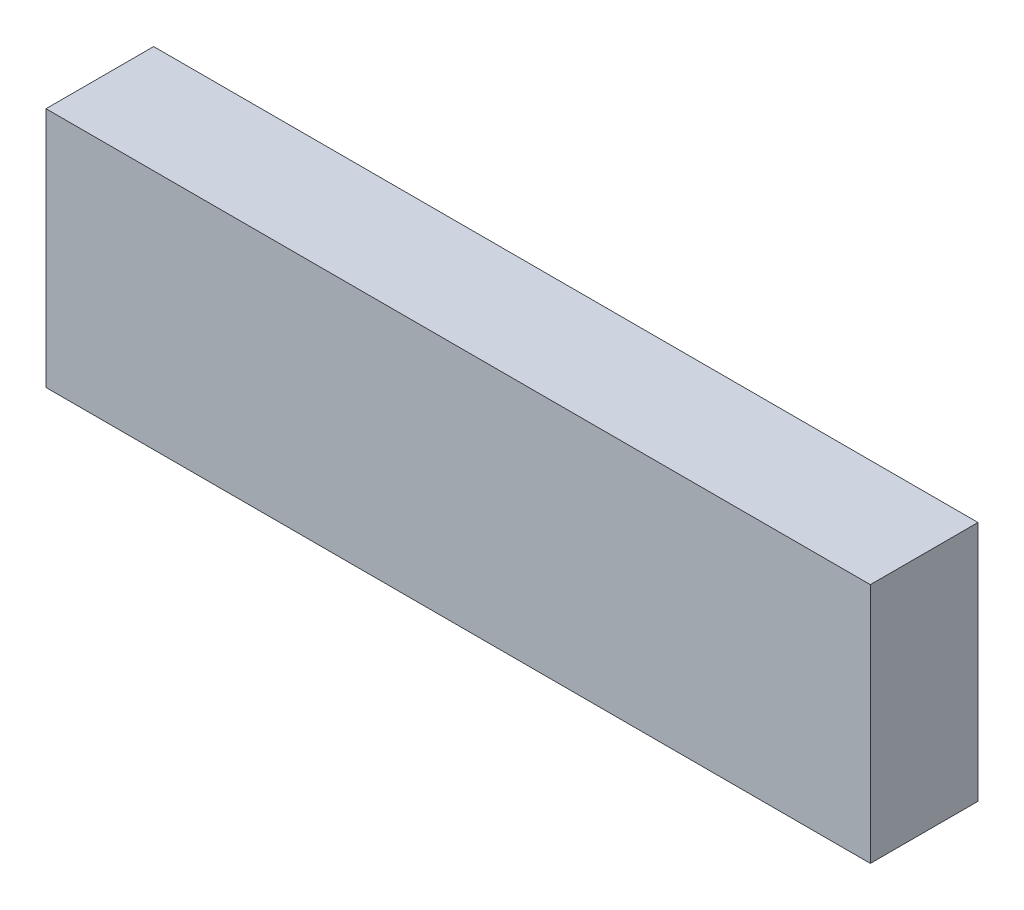
SolidWorks part; units mm, degrees
ref_plane "Front Plane" through (0, 0, 0) normal (0, 0, 1) x (1, 0, 0)
ref_plane "Top Plane" through (0, 0, 0) normal (0, 1, 0) x (1, 0, 0)
ref_plane "Right Plane" through (0, 0, 0) normal (1, 0, 0) x (0, 0, -1)
sketch "Sketch1" plane through (0, 0, 0) normal (0, 0, 1) x (1, 0, 0)
  line L1 (-60.5857, 19.8572) -> (207.4143, 19.8572)
  line L2 (-60.5857, 19.8572) -> (-60.5857, -58.6428)
  line L3 (-60.5857, -58.6428) -> (207.4143, -58.6428)
  line L4 (207.4143, 19.8572) -> (207.4143, -58.6428)
  dimension "D1" = 268
  dimension "D2" = 78.5
extrude "Boss-Extrude1" add sketch "Sketch1" along normal blind 35
